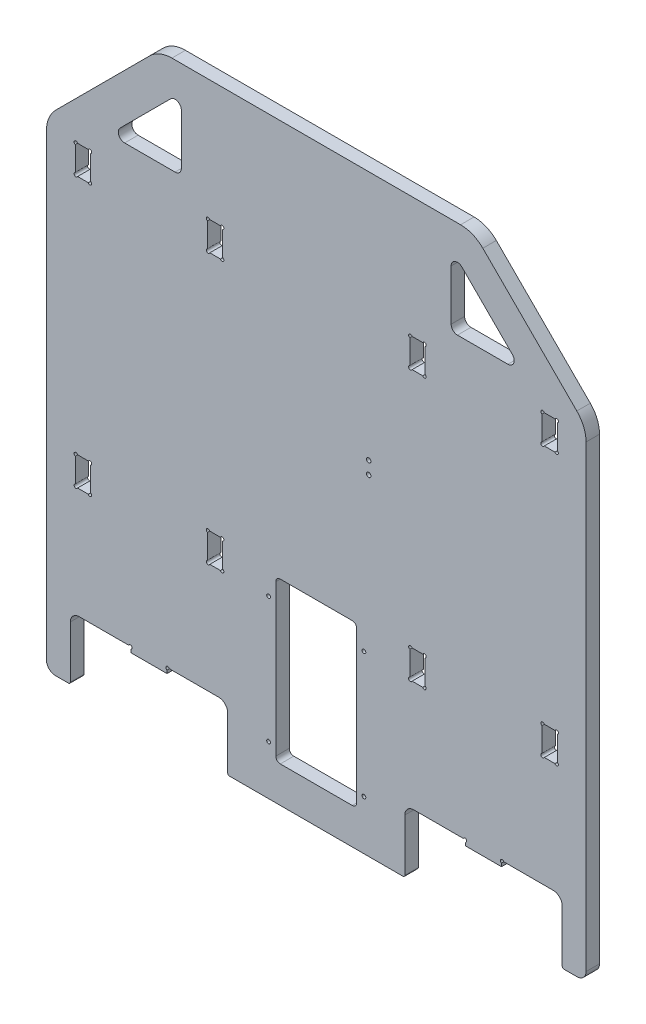
SolidWorks part; units mm, degrees
material "S355J2H"
ref_plane "Front Plane" through (0, 0, 0) normal (0, 0, 1) x (1, 0, 0)
ref_plane "Top Plane" through (0, 0, 0) normal (0, 1, 0) x (1, 0, 0)
ref_plane "Right Plane" through (0, 0, 0) normal (1, 0, 0) x (0, 0, -1)
sketch "Sketch1" plane through (0, 0, 0) normal (0, 0, 1) x (1, 0, 0)
  line L1 (-300, -270) -> (300, -270)
  line L2 (-300, -270) -> (-300, 270)
  line L3 (-300, 270) -> (300, 270)
  line L4 (300, -270) -> (300, 270)
  line L5 (-300, -270) -> (300, 270) construction
  line L6 (-300, 270) -> (300, -270) construction
  point P0 (0, 0)
  dimension "D1" = 540
  dimension "D2" = 600
extrude "Boss-Extrude1" add sketch "Sketch1" along normal blind 15
sketch "Sketch2" plane through (0, 0, 15) normal (0, 0, 1) x (1, 0, 0)
  line L0 (-300, -270) -> (300, -270) construction
  line L1 (-273.5, -270) -> (-98.5, -270)
  line L2 (-273.5, -270) -> (-273.5, -194.5)
  line L3 (-273.5, -194.5) -> (-98.5, -194.5)
  line L4 (-98.5, -270) -> (-98.5, -194.5)
  line L5 (-98.5, -194.5) -> (98.5, -194.5) construction
  line L6 (98.5, -270) -> (273.5, -270)
  line L7 (98.5, -270) -> (98.5, -194.5)
  line L8 (98.5, -194.5) -> (273.5, -194.5)
  line L9 (273.5, -270) -> (273.5, -194.5)
  line L10 (0, 0) -> (0, -194.5) construction
  line L11 (-186, -194.5) -> (-186, -85.9943) construction
  line L12 (186, -194.5) -> (186, -85.9943) construction
  dimension "D1" = 372
  dimension "D2" = 175
  dimension "D3" = 75.5
extrude "Cut-Extrude1" cut sketch "Sketch2" against normal through all
sketch "Sketch4" plane through (0, 0, 15) normal (0, 0, 1) x (1, 0, 0)
  line L1 (-268, 260.5) -> (-251, 260.5)
  line L2 (-268, 260.5) -> (-268, 228.5)
  line L3 (-268, 228.5) -> (-251, 228.5)
  line L4 (-251, 260.5) -> (-251, 228.5)
  line L5 (-121, 260.5) -> (-104, 260.5)
  line L6 (-121, 260.5) -> (-121, 228.5)
  line L7 (-121, 228.5) -> (-104, 228.5)
  line L8 (-104, 260.5) -> (-104, 228.5)
  line L9 (-268, -39.5) -> (-251, -39.5)
  line L10 (-268, -39.5) -> (-268, -71.5)
  line L11 (-268, -71.5) -> (-251, -71.5)
  line L12 (-251, -39.5) -> (-251, -71.5)
  line L13 (-121, -39.5) -> (-104, -39.5)
  line L14 (-121, -39.5) -> (-121, -71.5)
  line L15 (-121, -71.5) -> (-104, -71.5)
  line L16 (-104, -39.5) -> (-104, -71.5)
  line L18 (0, 0) -> (0, 331.9201) construction
  line L19 (104, -39.5) -> (104, -71.5)
  line L20 (121, -71.5) -> (104, -71.5)
  line L21 (121, -39.5) -> (121, -71.5)
  line L22 (121, -39.5) -> (104, -39.5)
  line L23 (251, -39.5) -> (251, -71.5)
  line L24 (268, -71.5) -> (251, -71.5)
  line L25 (268, -39.5) -> (268, -71.5)
  line L26 (268, -39.5) -> (251, -39.5)
  line L27 (104, 260.5) -> (104, 228.5)
  line L28 (121, 228.5) -> (104, 228.5)
  line L29 (121, 260.5) -> (121, 228.5)
  line L30 (121, 260.5) -> (104, 260.5)
  line L31 (251, 260.5) -> (251, 228.5)
  line L32 (268, 228.5) -> (251, 228.5)
  line L33 (268, 260.5) -> (268, 228.5)
  line L34 (268, 260.5) -> (251, 260.5)
  line L35 (-300, -270) -> (-273.5, -270) construction
  point P17 (-259.5, 260.5)
  point P18 (-251, 244.5)
  point P39 (-112.5, 260.5)
  point P40 (-286.75, -270)
  point P41 (-268, -55.5)
  dimension "D1" = 17
  dimension "D2" = 259.5
  dimension "D3" = 112.5
  dimension "D4" = 514.5
  dimension "D5" = 32
  dimension "D6" = 214.5
extrude "Cut-Extrude3" cut sketch "Sketch4" against normal through all
fillet "Fillet3" radius 10 4 edges at (273.5, -194.5, 7.5) (98.5, -194.5, 7.5) (-98.5, -194.5, 7.5) (-273.5, -194.5, 7.5)
sketch "Sketch5" plane through (0, 0, 15) normal (0, 0, 1) x (1, 0, 0)
  line L0 (-186, -194.5) -> (-186, -200.5) construction
  line L1 (-206, -194.5) -> (-166, -194.5)
  line L2 (-206, -194.5) -> (-206, -200.5)
  line L3 (-206, -200.5) -> (-166, -200.5)
  line L4 (-166, -194.5) -> (-166, -200.5)
  line L5 (166, -194.5) -> (206, -194.5)
  line L6 (166, -194.5) -> (166, -200.5)
  line L7 (166, -200.5) -> (206, -200.5)
  line L8 (206, -194.5) -> (206, -200.5)
  line L9 (-108.5, -194.5) -> (-263.5, -194.5) construction
  line L10 (186, -194.5) -> (186, -200.5) construction
  line L11 (263.5, -194.5) -> (108.5, -194.5) construction
  dimension "D1" = 40
  dimension "D2" = 6
extrude "Boss-Extrude2" add sketch "Sketch5" against normal up to surface (15 mm away) up to face at (112.5, -55.5, 0)
sketch "Sketch6" plane through (0, 0, 15) normal (0, 0, 1) x (1, 0, 0)
  line L0 (58.3, 117) -> (58.3, 103) construction
  line L1 (-300, 270) -> (-300, -270) construction
  line L2 (300, 270) -> (-300, 270) construction
  circle A0 centre (58.3, 117) radius 2.5
  circle A1 centre (58.3, 103) radius 2.5
  dimension "D1" = 358.3
  dimension "D4" = 5
  dimension "D2" = 153
  dimension "D3" = 14
extrude "Cut-Extrude4" cut sketch "Sketch6" against normal through all
cosmetic thread "Cosmetic Thread1" parameters "D2"=6
cosmetic thread "Cosmetic Thread2" parameters "D2"=6
sketch "Sketch7" plane through (0, 0, 15) normal (0, 0, 1) x (1, 0, 0)
  line L1 (-300, 270) -> (300, 270)
  line L2 (-300, 270) -> (-175, 395)
  line L3 (-175, 395) -> (175, 395)
  line L4 (300, 270) -> (175, 395)
  line L5 (0, 395) -> (0, 270) construction
  dimension "D1" = 125
  dimension "D2" = 45
extrude "Boss-Extrude3" add sketch "Sketch7" against normal blind 15
fillet "Fillet4" radius 35 4 edges at (175, 395, 7.5) (-175, 395, 7.5) (300, 270, 7.5) (-300, 270, 7.5)
sketch "Sketch8" plane through (0, 0, 15) normal (0, 0, 1) x (1, 0, 0)
  line L0 (-230, 286.967) -> (-150, 286.967)
  line L1 (-150, 286.967) -> (-150, 366.967)
  line L3 (-150, 366.967) -> (-230, 286.967)
  line L4 (-185.2513, 384.7487) -> (-289.7487, 280.2513) construction
  line L5 (160.5025, 395) -> (-160.5025, 395) construction
  line L6 (0, 395) -> (0, 0) construction
  line L7 (150, 366.967) -> (230, 286.967)
  line L9 (150, 286.967) -> (150, 366.967)
  line L10 (230, 286.967) -> (150, 286.967)
  dimension "D1" = 37.5
  dimension "D2" = 150
  dimension "D3" = 80
extrude "Cut-Extrude5" cut sketch "Sketch8" against normal blind 15
fillet "Fillet5" radius 7 6 edges at (230, 286.967, 7.5) (150, 286.967, 7.5) (-150, 286.967, 7.5) (-230, 286.967, 7.5) (150, 366.967, 7.5) (-150, 366.967, 7.5)
sketch "Sketch9" plane through (0, 0, 15) normal (0, 0, 1) x (1, 0, 0)
  line L0 (-300, 255.5025) -> (-300, -270) construction
  line L1 (300, -270) -> (-300, -270)
  line L2 (300, -270) -> (300, -264.5)
  line L3 (300, -264.5) -> (-300, -264.5)
  line L4 (-300, -270) -> (-300, -264.5)
  line L5 (300, -270) -> (300, 255.5025) construction
  dimension "D1" = 5.5
extrude "Cut-Extrude6" cut sketch "Sketch9" against normal through all
fillet "Fillet7" radius 10 2 edges at (300, -264.5, 7.5) (-300, -264.5, 7.5)
fillet "Fillet8" radius 2 4 edges at (273.5, -264.5, 7.5) (98.5, -264.5, 7.5) (-98.5, -264.5, 7.5) (-273.5, -264.5, 7.5)
sketch "Sketch10" plane through (0, 0, 15) normal (0, 0, 1) x (1, 0, 0)
  line L1 (-45, -224.5) -> (45, -224.5)
  line L2 (-45, -224.5) -> (-45, -46.5)
  line L3 (-45, -46.5) -> (45, -46.5)
  line L4 (45, -224.5) -> (45, -46.5)
  line L6 (0, -224.5) -> (0, -264.5) construction
  line L7 (96.5, -264.5) -> (-96.5, -264.5) construction
  dimension "D1" = 178
  dimension "D2" = 40
  dimension "D3" = 90
extrude "Cut-Extrude7" cut sketch "Sketch10" against normal blind 15
fillet "Fillet9" radius 5 4 edges at (45, -46.5, 7.5) (-45, -46.5, 7.5) (45, -224.5, 7.5) (-45, -224.5, 7.5)
sketch "Sketch11" plane through (0, 0, 15) normal (0, 0, 1) x (1, 0, 0)
  line L0 (-45, -135.5) -> (45, -135.5) construction
  line L1 (-53, -69.5) -> (53, -69.5) construction
  line L2 (-53, -69.5) -> (-53, -209.5) construction
  line L3 (-53, -209.5) -> (53, -209.5) construction
  line L4 (53, -69.5) -> (53, -209.5) construction
  line L5 (-53, -69.5) -> (53, -209.5) construction
  line L6 (-53, -209.5) -> (53, -69.5) construction
  line L7 (-45, -51.5) -> (-45, -219.5) construction
  line L8 (45, -219.5) -> (45, -51.5) construction
  line L9 (96.5, -264.5) -> (-96.5, -264.5) construction
  line L10 (0, -139.5) -> (0, -264.5) construction
  circle A0 centre (53, -69.5) radius 2.1
  circle A1 centre (53, -209.5) radius 2.1
  circle A2 centre (-53, -209.5) radius 2.1
  circle A3 centre (-53, -69.5) radius 2.1
  point P0 (0, -139.5)
  dimension "D3" = 4.2
  dimension "D1" = 106
  dimension "D2" = 140
  dimension "D4" = 55
extrude "Cut-Extrude8" cut sketch "Sketch11" against normal blind 15
sketch "Sketch12" plane through (0, 0, 15) normal (0, 0, 1) x (1, 0, 0)
  line L0 (-251.7071, 259.7929) -> (-251, 260.5) construction
  line L1 (-251, 260.5) -> (-268, 260.5) construction
  line L2 (-259.5, 260.5) -> (-259.5, 228.5) construction
  line L3 (-268, 228.5) -> (-251, 228.5) construction
  line L4 (-268, 244.5) -> (-251, 244.5) construction
  line L5 (-268, 260.5) -> (-268, 228.5) construction
  line L6 (-251, 228.5) -> (-251, 260.5) construction
  line L7 (-267.2929, 259.7929) -> (-268, 260.5) construction
  line L8 (-267.2929, 229.2071) -> (-268, 228.5) construction
  line L9 (-251.7071, 229.2071) -> (-251, 228.5) construction
  line L10 (-104.7071, 259.7929) -> (-104, 260.5) construction
  line L11 (-112.5, 260.5) -> (-112.5, 228.5) construction
  line L12 (-121, 244.5) -> (-104, 244.5) construction
  line L13 (-120.2929, 259.7929) -> (-121, 260.5) construction
  line L14 (-120.2929, 229.2071) -> (-121, 228.5) construction
  line L15 (-104.7071, 229.2071) -> (-104, 228.5) construction
  line L16 (-104, 228.5) -> (-104, 260.5) construction
  line L17 (-104, 260.5) -> (-121, 260.5) construction
  line L18 (-121, 228.5) -> (-104, 228.5) construction
  line L19 (-121, 260.5) -> (-121, 228.5) construction
  line L20 (-268, -39.5) -> (-268, 228.5) construction
  line L21 (-268, 94.5) -> (122.3898, 94.5) construction
  line L22 (-104.7071, -40.2071) -> (-104, -39.5) construction
  line L23 (-120.2929, -40.2071) -> (-121, -39.5) construction
  line L24 (-120.2929, -70.7929) -> (-121, -71.5) construction
  line L25 (-121, -55.5) -> (-104, -55.5) construction
  line L26 (-112.5, -71.5) -> (-112.5, -39.5) construction
  line L27 (-104.7071, -70.7929) -> (-104, -71.5) construction
  line L28 (-251.7071, -40.2071) -> (-251, -39.5) construction
  line L29 (-267.2929, -40.2071) -> (-268, -39.5) construction
  line L30 (-267.2929, -70.7929) -> (-268, -71.5) construction
  line L31 (-268, -55.5) -> (-251, -55.5) construction
  line L32 (-259.5, -71.5) -> (-259.5, -39.5) construction
  line L33 (-251.7071, -70.7929) -> (-251, -71.5) construction
  line L34 (0, 0) -> (0, 357.0085) construction
  line L35 (251.7071, -70.7929) -> (251, -71.5) construction
  line L36 (259.5, -71.5) -> (259.5, -39.5) construction
  line L37 (268, -55.5) -> (251, -55.5) construction
  line L38 (267.2929, -70.7929) -> (268, -71.5) construction
  line L39 (267.2929, -40.2071) -> (268, -39.5) construction
  line L40 (251.7071, -40.2071) -> (251, -39.5) construction
  line L41 (104.7071, -70.7929) -> (104, -71.5) construction
  line L42 (112.5, -71.5) -> (112.5, -39.5) construction
  line L43 (121, -55.5) -> (104, -55.5) construction
  line L44 (120.2929, -70.7929) -> (121, -71.5) construction
  line L45 (120.2929, -40.2071) -> (121, -39.5) construction
  line L46 (104.7071, -40.2071) -> (104, -39.5) construction
  line L47 (268, -39.5) -> (268, 228.5) construction
  line L48 (104.7071, 229.2071) -> (104, 228.5) construction
  line L49 (120.2929, 229.2071) -> (121, 228.5) construction
  line L50 (120.2929, 259.7929) -> (121, 260.5) construction
  line L51 (121, 244.5) -> (104, 244.5) construction
  line L52 (112.5, 260.5) -> (112.5, 228.5) construction
  line L53 (104.7071, 259.7929) -> (104, 260.5) construction
  line L54 (251.7071, 229.2071) -> (251, 228.5) construction
  line L55 (267.2929, 229.2071) -> (268, 228.5) construction
  line L56 (267.2929, 259.7929) -> (268, 260.5) construction
  line L57 (268, 244.5) -> (251, 244.5) construction
  line L58 (259.5, 260.5) -> (259.5, 228.5) construction
  line L59 (251.7071, 259.7929) -> (251, 260.5) construction
  circle A0 centre (-251.7071, 259.7929) radius 2
  circle A1 centre (-267.2929, 259.7929) radius 2
  circle A2 centre (-267.2929, 229.2071) radius 2
  circle A3 centre (-251.7071, 229.2071) radius 2
  circle A4 centre (-104.7071, 259.7929) radius 2
  circle A5 centre (-120.2929, 259.7929) radius 2
  circle A6 centre (-120.2929, 229.2071) radius 2
  circle A7 centre (-104.7071, 229.2071) radius 2
  circle A8 centre (-104.7071, -40.2071) radius 2
  circle A9 centre (-120.2929, -40.2071) radius 2
  circle A10 centre (-120.2929, -70.7929) radius 2
  circle A11 centre (-104.7071, -70.7929) radius 2
  circle A12 centre (-251.7071, -40.2071) radius 2
  circle A13 centre (-267.2929, -40.2071) radius 2
  circle A14 centre (-267.2929, -70.7929) radius 2
  circle A15 centre (-251.7071, -70.7929) radius 2
  circle A16 centre (251.7071, -70.7929) radius 2
  circle A17 centre (267.2929, -70.7929) radius 2
  circle A18 centre (267.2929, -40.2071) radius 2
  circle A19 centre (251.7071, -40.2071) radius 2
  circle A20 centre (104.7071, -70.7929) radius 2
  circle A21 centre (120.2929, -70.7929) radius 2
  circle A22 centre (120.2929, -40.2071) radius 2
  circle A23 centre (104.7071, -40.2071) radius 2
  circle A24 centre (104.7071, 229.2071) radius 2
  circle A25 centre (120.2929, 229.2071) radius 2
  circle A26 centre (120.2929, 259.7929) radius 2
  circle A27 centre (104.7071, 259.7929) radius 2
  circle A28 centre (251.7071, 229.2071) radius 2
  circle A29 centre (267.2929, 229.2071) radius 2
  circle A30 centre (267.2929, 259.7929) radius 2
  circle A31 centre (251.7071, 259.7929) radius 2
  dimension "D1" = 45
  dimension "D3" = 4
  dimension "D5" = 4
  dimension "D2" = 1
  dimension "D4" = 1
  dimension "D6" = 45
extrude "Cut-Extrude9" cut sketch "Sketch12" against normal through all
sketch "Sketch13" plane through (0, 0, 15) normal (0, 0, 1) x (1, 0, 0)
  line L0 (-206.7071, -195.2071) -> (-206, -194.5) construction
  line L1 (-206, -194.5) -> (-263.5, -194.5) construction
  line L2 (-186, -200.5) -> (-186, -177.0161) construction
  line L3 (-206, -200.5) -> (-166, -200.5) construction
  line L4 (-165.2929, -195.2071) -> (-166, -194.5) construction
  line L5 (0, 0) -> (0, -332.4682) construction
  line L6 (165.2929, -195.2071) -> (166, -194.5) construction
  line L7 (186, -200.5) -> (186, -177.0161) construction
  line L8 (206.7071, -195.2071) -> (206, -194.5) construction
  circle A0 centre (-206.7071, -195.2071) radius 2
  circle A1 centre (-165.2929, -195.2071) radius 2
  circle A2 centre (165.2929, -195.2071) radius 2
  circle A3 centre (206.7071, -195.2071) radius 2
  dimension "D2" = 4
  dimension "D1" = 1
  dimension "D3" = 135
extrude "Cut-Extrude10" cut sketch "Sketch13" against normal through all
